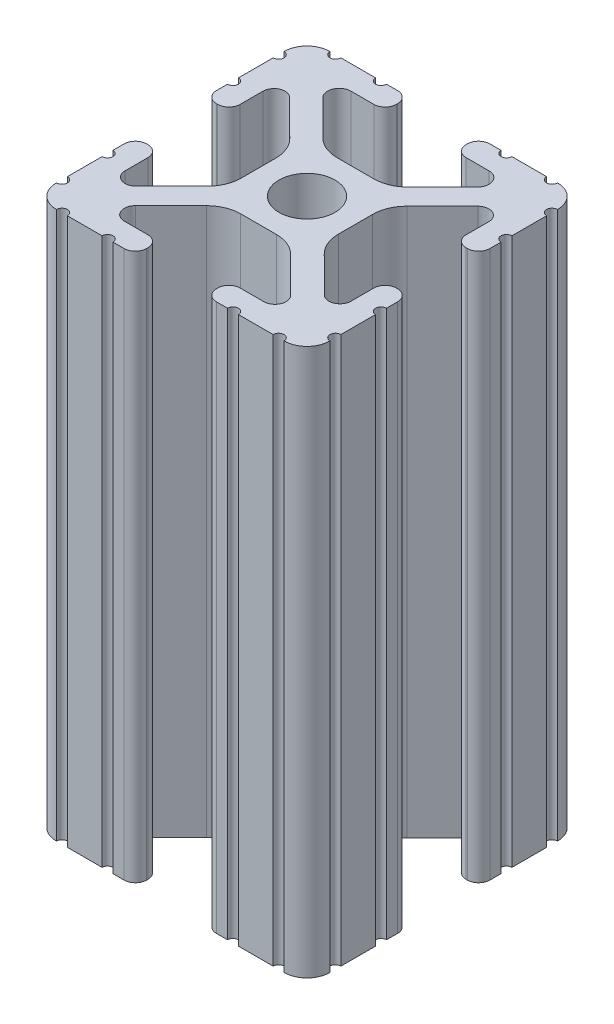
SolidWorks part; units mm, degrees
ref_plane "Front" through (0, 0, 0) normal (0, 0, 1) x (1, 0, 0)
ref_plane "Top" through (0, 0, 0) normal (0, 1, 0) x (1, 0, 0)
ref_plane "Right" through (0, 0, 0) normal (1, 0, 0) x (0, 0, -1)
sketch "Sketch1" plane through (0, 0, 0) normal (0, 0, 1) x (1, 0, 0)
  line L0 (0, 0) -> (0, 50.8)
  dimension "D1" = 50.8
other "10 1010 PROFILE(1)"
ref_plane "Plane1" through (0, 0, 0) normal (0, 1, 0) x (-1, 0, 0)
sketch "Sketch12" plane through (0, 0, 0) normal (0, 1, 0) x (-1, 0, 0)
  line L1 (12.7, 12.7) -> (-12.7, 12.7) construction
  line L2 (12.7, 12.7) -> (12.7, -12.7) construction
  line L3 (12.7, -12.7) -> (-12.7, -12.7) construction
  line L4 (-12.7, 12.7) -> (-12.7, -12.7) construction
  line L5 (12.7, 12.7) -> (-12.7, -12.7) construction
  line L6 (12.7, -12.7) -> (-12.7, 12.7) construction
  line L88 (-1.7093, -4.4958) -> (1.7093, -4.4958)
  line L89 (3.9523, -5.4237) -> (7.1797, -8.6452)
  line L90 (6.4164, -10.4902) -> (4.2875, -10.4902)
  line L91 (3.2385, -11.5392) -> (3.2385, -11.651)
  line L92 (4.2875, -12.7) -> (5.3171, -12.7)
  line L93 (6.3331, -12.7) -> (9.5504, -12.7)
  line L94 (12.7, -9.5504) -> (12.7, -6.3331)
  line L95 (12.7, -5.3171) -> (12.7, -4.2875)
  line L96 (11.651, -3.2385) -> (11.5392, -3.2385)
  line L97 (10.4902, -4.2875) -> (10.4902, -6.4021)
  line L98 (8.737, -7.1292) -> (5.4405, -3.8388)
  line L99 (4.5085, -1.5917) -> (4.5085, 1.5917)
  line L100 (5.4405, 3.8388) -> (8.737, 7.1292)
  line L101 (10.4902, 6.4021) -> (10.4902, 4.2875)
  line L102 (11.5392, 3.2385) -> (11.651, 3.2385)
  line L103 (12.7, 4.2875) -> (12.7, 5.3171)
  line L104 (12.7, 6.3331) -> (12.7, 9.5504)
  line L105 (9.5504, 12.7) -> (6.3331, 12.7)
  line L106 (5.3171, 12.7) -> (4.2875, 12.7)
  line L107 (3.2384, 11.651) -> (3.2384, 11.5392)
  line L108 (4.2875, 10.4902) -> (6.4768, 10.4902)
  line L109 (7.2072, 8.7245) -> (3.9003, 5.4237)
  line L110 (1.6573, 4.4958) -> (-1.6573, 4.4958)
  line L111 (-3.9003, 5.4237) -> (-7.2072, 8.7245)
  line L112 (-6.4768, 10.4902) -> (-4.2875, 10.4902)
  line L113 (-3.2384, 11.5392) -> (-3.2384, 11.651)
  line L114 (-4.2875, 12.7) -> (-5.3171, 12.7)
  line L115 (-6.3331, 12.7) -> (-9.5504, 12.7)
  line L116 (-12.7, 9.5504) -> (-12.7, 6.3331)
  line L117 (-12.7, 5.3171) -> (-12.7, 4.2875)
  line L118 (-11.651, 3.2385) -> (-11.5392, 3.2385)
  line L119 (-10.4902, 4.2875) -> (-10.4902, 6.4021)
  line L120 (-8.737, 7.1292) -> (-5.4405, 3.8388)
  line L121 (-4.5085, 1.5917) -> (-4.5085, -1.5917)
  line L122 (-5.4405, -3.8388) -> (-8.737, -7.1292)
  line L123 (-10.4902, -6.4021) -> (-10.4902, -4.2875)
  line L124 (-11.5392, -3.2385) -> (-11.651, -3.2385)
  line L125 (-12.7, -4.2875) -> (-12.7, -5.3171)
  line L126 (-12.7, -6.3331) -> (-12.7, -9.5504)
  line L127 (-9.5504, -12.7) -> (-6.3331, -12.7)
  line L128 (-5.3171, -12.7) -> (-4.2875, -12.7)
  line L129 (-3.2385, -11.651) -> (-3.2385, -11.5392)
  line L130 (-4.2875, -10.4902) -> (-6.4164, -10.4902)
  line L131 (-7.1797, -8.6452) -> (-3.9523, -5.4237)
  circle A1 centre (0, 0) radius 2.6035
  arc A104 (-1.7093, -4.4958) -> (-3.9523, -5.4237) centre (-1.7093, -7.6708) ccw
  arc A105 (3.9523, -5.4237) -> (1.7093, -4.4958) centre (1.7093, -7.6708) ccw
  arc A106 (6.4164, -10.4902) -> (7.1797, -8.6452) centre (6.4164, -9.4098) ccw
  arc A107 (4.2875, -10.4902) -> (3.2385, -11.5392) centre (4.2875, -11.5392) ccw
  arc A108 (3.2385, -11.651) -> (4.2875, -12.7) centre (4.2875, -11.651) ccw
  arc A109 (6.3331, -12.7) -> (5.3171, -12.7) centre (5.8251, -12.7) ccw
  arc A110 (10.5664, -12.6998) -> (9.5504, -12.7) centre (10.0584, -12.7) ccw
  arc A111 (10.5664, -12.6998) -> (12.6998, -10.5664) centre (10.5918, -10.5918) ccw
  arc A112 (12.7, -9.5504) -> (12.6998, -10.5664) centre (12.7, -10.0584) ccw
  arc A113 (12.7, -5.3171) -> (12.7, -6.3331) centre (12.7, -5.8251) ccw
  arc A114 (12.7, -4.2875) -> (11.651, -3.2385) centre (11.651, -4.2875) ccw
  arc A115 (11.5392, -3.2385) -> (10.4902, -4.2875) centre (11.5392, -4.2875) ccw
  arc A116 (8.737, -7.1292) -> (10.4902, -6.4021) centre (9.4628, -6.4021) ccw
  arc A117 (4.5085, -1.5917) -> (5.4405, -3.8388) centre (7.6835, -1.5917) ccw
  arc A118 (5.4405, 3.8388) -> (4.5085, 1.5917) centre (7.6835, 1.5917) ccw
  arc A119 (10.4902, 6.4021) -> (8.737, 7.1292) centre (9.4628, 6.4021) ccw
  arc A120 (10.4902, 4.2875) -> (11.5392, 3.2385) centre (11.5392, 4.2875) ccw
  arc A121 (11.651, 3.2385) -> (12.7, 4.2875) centre (11.651, 4.2875) ccw
  arc A122 (12.7, 6.3331) -> (12.7, 5.3171) centre (12.7, 5.8251) ccw
  arc A123 (12.6998, 10.5664) -> (12.7, 9.5504) centre (12.7, 10.0584) ccw
  arc A124 (12.6998, 10.5664) -> (10.5664, 12.6998) centre (10.5918, 10.5918) ccw
  arc A125 (9.5504, 12.7) -> (10.5664, 12.6998) centre (10.0584, 12.7) ccw
  arc A126 (5.3171, 12.7) -> (6.3331, 12.7) centre (5.8251, 12.7) ccw
  arc A127 (4.2875, 12.7) -> (3.2384, 11.651) centre (4.2875, 11.651) ccw
  arc A128 (3.2384, 11.5392) -> (4.2875, 10.4902) centre (4.2875, 11.5392) ccw
  arc A129 (7.2072, 8.7245) -> (6.4768, 10.4902) centre (6.4768, 9.4563) ccw
  arc A130 (1.6573, 4.4958) -> (3.9003, 5.4237) centre (1.6573, 7.6708) ccw
  arc A131 (-3.9003, 5.4237) -> (-1.6573, 4.4958) centre (-1.6573, 7.6708) ccw
  arc A132 (-6.4768, 10.4902) -> (-7.2072, 8.7245) centre (-6.4768, 9.4563) ccw
  arc A133 (-4.2875, 10.4902) -> (-3.2384, 11.5392) centre (-4.2875, 11.5392) ccw
  arc A134 (-3.2384, 11.651) -> (-4.2875, 12.7) centre (-4.2875, 11.651) ccw
  arc A135 (-6.3331, 12.7) -> (-5.3171, 12.7) centre (-5.8251, 12.7) ccw
  arc A136 (-10.5664, 12.6998) -> (-9.5504, 12.7) centre (-10.0584, 12.7) ccw
  arc A137 (-10.5664, 12.6998) -> (-12.6998, 10.5664) centre (-10.5918, 10.5918) ccw
  arc A138 (-12.7, 9.5504) -> (-12.6998, 10.5664) centre (-12.7, 10.0584) ccw
  arc A139 (-12.7, 5.3171) -> (-12.7, 6.3331) centre (-12.7, 5.8251) ccw
  arc A140 (-12.7, 4.2875) -> (-11.651, 3.2385) centre (-11.651, 4.2875) ccw
  arc A141 (-11.5392, 3.2385) -> (-10.4902, 4.2875) centre (-11.5392, 4.2875) ccw
  arc A142 (-8.737, 7.1292) -> (-10.4902, 6.4021) centre (-9.4628, 6.4021) ccw
  arc A143 (-4.5085, 1.5917) -> (-5.4405, 3.8388) centre (-7.6835, 1.5917) ccw
  arc A144 (-5.4405, -3.8388) -> (-4.5085, -1.5917) centre (-7.6835, -1.5917) ccw
  arc A145 (-10.4902, -6.4021) -> (-8.737, -7.1292) centre (-9.4628, -6.4021) ccw
  arc A146 (-10.4902, -4.2875) -> (-11.5392, -3.2385) centre (-11.5392, -4.2875) ccw
  arc A147 (-11.651, -3.2385) -> (-12.7, -4.2875) centre (-11.651, -4.2875) ccw
  arc A148 (-12.7, -6.3331) -> (-12.7, -5.3171) centre (-12.7, -5.8251) ccw
  arc A149 (-12.6998, -10.5664) -> (-12.7, -9.5504) centre (-12.7, -10.0584) ccw
  arc A150 (-12.6998, -10.5664) -> (-10.5664, -12.6998) centre (-10.5918, -10.5918) ccw
  arc A151 (-9.5504, -12.7) -> (-10.5664, -12.6998) centre (-10.0584, -12.7) ccw
  arc A152 (-5.3171, -12.7) -> (-6.3331, -12.7) centre (-5.8251, -12.7) ccw
  arc A153 (-4.2875, -12.7) -> (-3.2385, -11.651) centre (-4.2875, -11.651) ccw
  arc A154 (-3.2385, -11.5392) -> (-4.2875, -10.4902) centre (-4.2875, -11.5392) ccw
  arc A155 (-7.1797, -8.6452) -> (-6.4164, -10.4902) centre (-6.4164, -9.4098) ccw
  point P3 (0, 0)
  point P21 (-12.7, 0)
  point P22 (0, 12.7)
  point P25 (12.7, 0)
  point P28 (0, -12.7)
  point P30 (-12.7, -12.7)
  point P33 (12.7, -12.7)
  point P37 (12.7, 12.7)
  point P40 (-12.7, 12.7)
  point P43 (0, 0)
  dimension "D1" = 25.4
